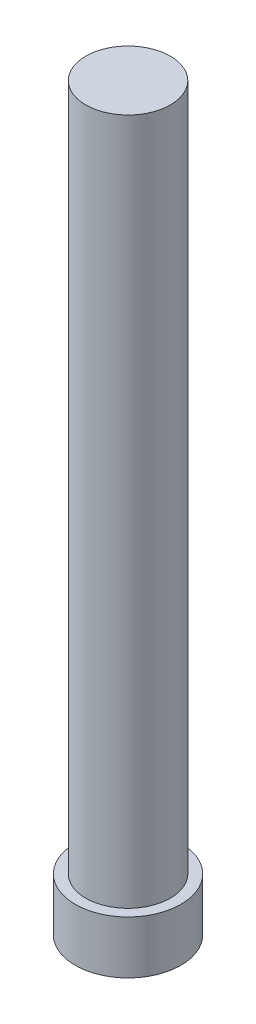
SolidWorks part; units mm, degrees
ref_plane "前视基准面" through (0, 0, 0) normal (0, 0, 1) x (1, 0, 0)
ref_plane "上视基准面" through (0, 0, 0) normal (0, 1, 0) x (1, 0, 0)
ref_plane "右视基准面" through (0, 0, 0) normal (1, 0, 0) x (0, 0, -1)
sketch "草图1" plane through (0, 0, 0) normal (0, 1, 0) x (1, 0, 0)
  circle A0 centre (0, 0) radius 4
extrude "凸台-拉伸1" add sketch "草图1" along normal blind 65
sketch "草图2" plane through (0, 0, 0) normal (0, -1, 0) x (1, 0, 0)
  circle A0 centre (0, 0) radius 5
extrude "凸台-拉伸2" add sketch "草图2" along normal blind 5
